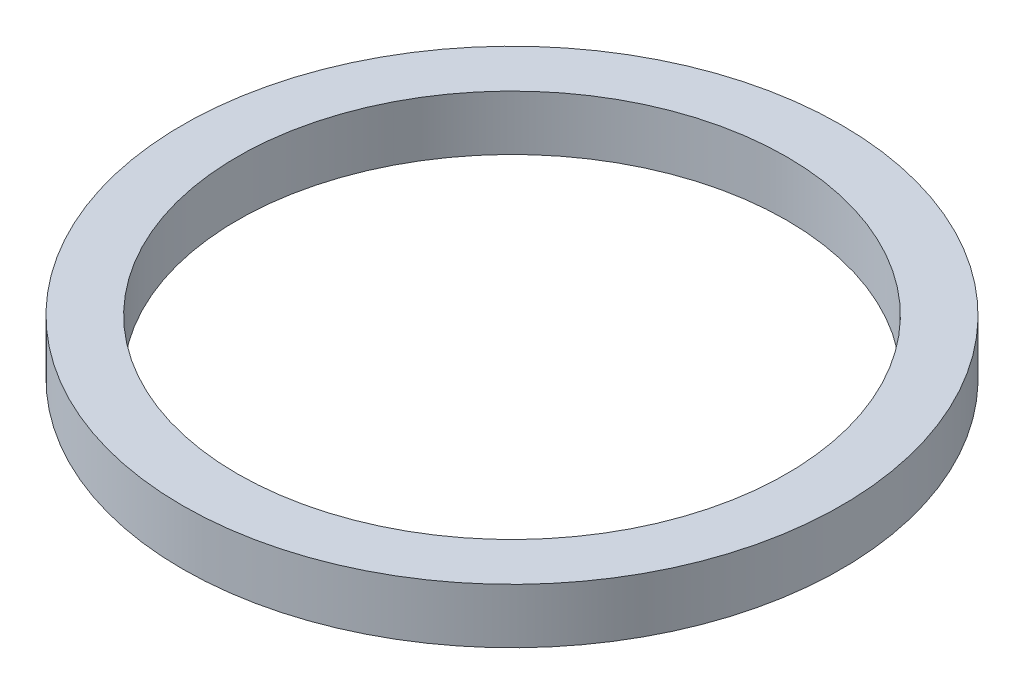
SolidWorks part; units mm, degrees
ref_plane "Front Plane" through (0, 0, 0) normal (0, 0, 1) x (1, 0, 0)
ref_plane "Top Plane" through (0, 0, 0) normal (0, 1, 0) x (1, 0, 0)
ref_plane "Right Plane" through (0, 0, 0) normal (1, 0, 0) x (0, 0, -1)
sketch "Sketch1" plane through (0, 0, 0) normal (0, 1, 0) x (1, 0, 0)
  circle A0 centre (-59.6666, 25.7617) radius 2.4
  circle A1 centre (-59.6666, 25.7617) radius 2
extrude "Boss-Extrude2" add sketch "Sketch1" along normal blind 0.4 contours A0 | A1
